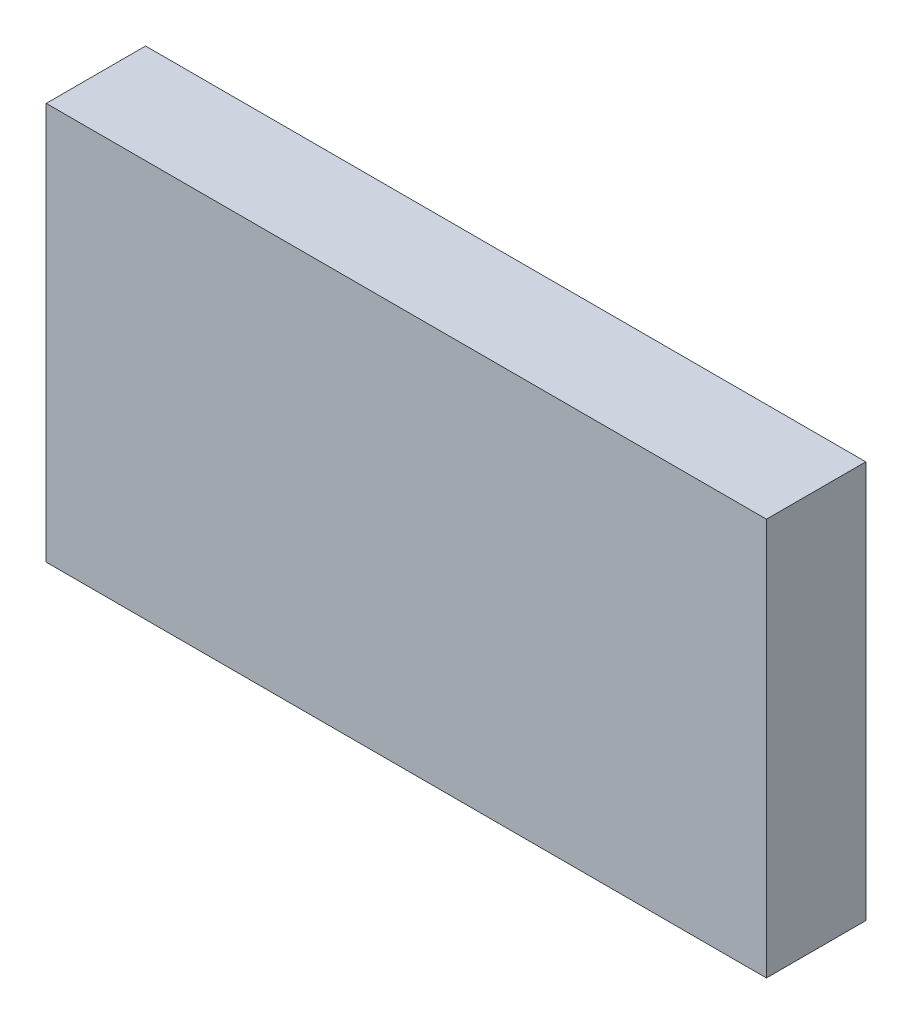
SolidWorks part; units mm, degrees
ref_plane "前视基准面" through (0, 0, 0) normal (0, 0, 1) x (1, 0, 0)
ref_plane "上视基准面" through (0, 0, 0) normal (0, 1, 0) x (1, 0, 0)
ref_plane "右视基准面" through (0, 0, 0) normal (1, 0, 0) x (0, 0, -1)
other "Configuration Table"
sketch "草图1" plane through (0, 0, 0) normal (0, 0, 1) x (1, 0, 0)
  line L1 (-72.5, -40) -> (72.5, -40)
  line L2 (-72.5, -40) -> (-72.5, 40)
  line L3 (-72.5, 40) -> (72.5, 40)
  line L4 (72.5, -40) -> (72.5, 40)
  line L5 (-72.5, -40) -> (72.5, 40) construction
  line L6 (-72.5, 40) -> (72.5, -40) construction
  point P0 (0, 0)
extrude "凸台-拉伸1" add sketch "草图1" along normal blind 20
